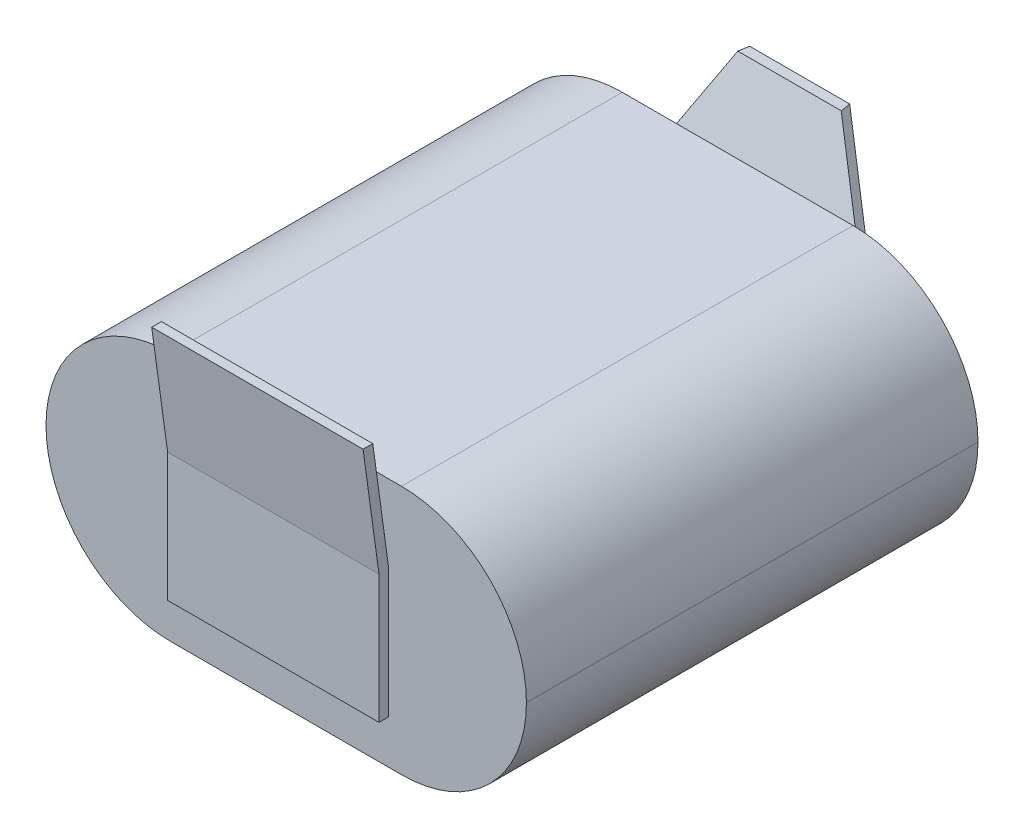
SolidWorks part; units mm, degrees
ref_plane "Plan de face" through (0, 0, 0) normal (0, 0, 1) x (1, 0, 0)
ref_plane "Plan de dessus" through (0, 0, 0) normal (0, 1, 0) x (1, 0, 0)
ref_plane "Plan de droite" through (0, 0, 0) normal (1, 0, 0) x (0, 0, -1)
sketch "Esquisse1" plane through (0, 0, 0) normal (0, 0, 1) x (1, 0, 0)
  line L7 (-8.8391, -7.6) -> (3.1709, -7.6)
  line L8 (9.6709, -14.11) -> (9.6709, -14.1)
  line L9 (-8.8291, -20.6) -> (3.1809, -20.6)
  line L10 (-15.3291, -14.1) -> (-15.3291, -14.09)
  arc A4 (9.6709, -14.1) -> (3.1709, -7.6) centre (3.1709, -14.1) ccw
  arc A5 (3.1809, -20.6) -> (9.6709, -14.11) centre (3.1809, -14.11) ccw
  arc A6 (-15.3291, -14.1) -> (-8.8291, -20.6) centre (-8.8291, -14.1) ccw
  arc A7 (-8.8391, -7.6) -> (-15.3291, -14.09) centre (-8.8391, -14.09) ccw
extrude "Extrusion1" add sketch "Esquisse1" against normal blind 23.5
ref_plane "Plan4" through (-3, 0, 0) normal (1, 0, 0) x (0, 0, -1)
sketch "Esquisse2" plane through (-3, 0, 0) normal (1, 0, 0) x (0, 0, -1)
  line L0 (0, -18.3247) -> (0, -11.6079)
  line L1 (0, -14.11) -> (0, -20.6) construction
  line L2 (0, -7.6) -> (0, -14.1) construction
  line L3 (0, -11.6079) -> (-0.8242, -5.6)
  line L5 (-0.5, -18.3247) -> (-0.5, -11.642)
  line L6 (-0.5, -11.642) -> (-1.3289, -5.6)
  line L7 (-0.5, -18.3247) -> (0, -18.3247)
  line L8 (-0.8242, -5.6) -> (-1.3289, -5.6)
  line L9 (-0.5, -11.642) -> (-1.3196, -5.668) construction
  dimension "D1" = 0.5
extrude "Extrusion2" add sketch "Esquisse2" along normal mid plane 11
sketch "Esquisse3" plane through (-3, 0, 0) normal (1, 0, 0) x (0, 0, -1)
  line L0 (23.5, -18.3247) -> (24, -18.3247)
  line L1 (23.5, -20.6) -> (23.5, -14.11) construction
  line L2 (24, -18.3247) -> (24, -14.11)
  line L3 (24, -14.11) -> (26.891, -5.6)
  line L5 (23.5, -18.3247) -> (23.5, -14.0274)
  line L6 (23.5, -14.0274) -> (26.3629, -5.6)
  line L7 (26.891, -5.6) -> (26.3629, -5.6)
  line L8 (23.5, -14.0274) -> (26.4176, -5.4392) construction
  dimension "D1" = 0.5
extrude "Extrusion3" add sketch "Esquisse3" along normal mid plane 11
sketch "Esquisse4" plane through (0, -8.7695, -25.8142) normal (0, -0.3217, -0.9469) x (-1, 0, 0)
  line L0 (3, 3.3475) -> (3, -6.9889) construction
  line L1 (-2.5, 3.3475) -> (8.5, 3.3475) construction
  line L2 (0.6454, 3.8348) -> (-2.5, -2.3215)
  line L3 (-2.5, -5.6402) -> (-2.5, 3.3475) construction
  line L4 (-2.5, -2.3215) -> (-3.2576, -2.3215)
  line L5 (-3.2576, -2.3215) -> (-3.2576, 4.72)
  line L6 (8.5, -2.3215) -> (9.2576, -2.3215)
  line L7 (5.3546, 3.8348) -> (8.5, -2.3215)
  line L8 (9.2576, -2.3215) -> (9.2576, 4.72)
  line L9 (0.6454, 3.8348) -> (5.3546, 3.8348)
  line L10 (-3.2576, 4.72) -> (9.2576, 4.72)
extrude "Enlèv. mat.-Extru.1" cut sketch "Esquisse4" against normal blind 0.5
